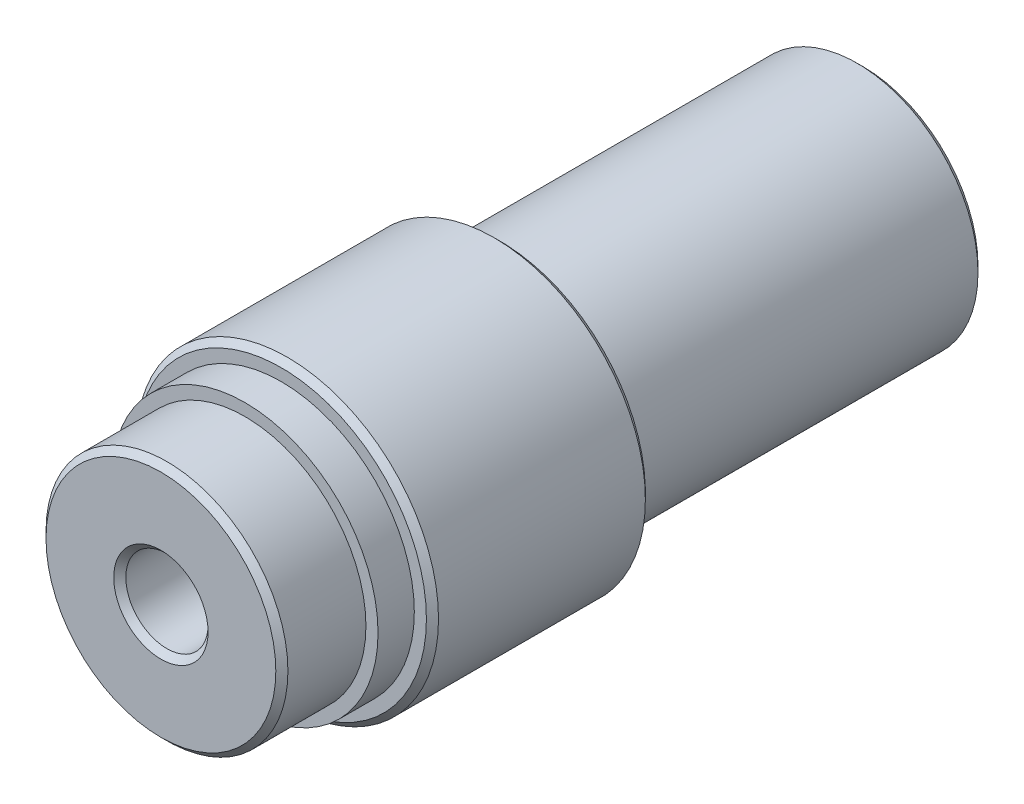
SolidWorks part; units mm, degrees
material "AISI 304"
ref_plane "Front" through (0, 0, 0) normal (0, 0, 1) x (1, 0, 0)
ref_plane "Top" through (0, 0, 0) normal (0, 1, 0) x (1, 0, 0)
ref_plane "Right" through (0, 0, 0) normal (1, 0, 0) x (0, 0, -1)
sketch "Çizim1" plane through (0, 0, 0) normal (1, 0, 0) x (0, 0, -1)
  line L0 (-29.025, 0) -> (29.025, 0)
  point P4 (0, 0)
  dimension "D1" = 58.05
other "Mil - configured CAP=25(1)"
ref_plane "Düzlem1" through (0, 0, 29.025) normal (0, 0, -1) x (0, 1, 0)
sketch "Sketch1" plane through (0, 0, 29.025) normal (0, 0, -1) x (0, 1, 0)
  circle A0 centre (0, 0) radius 12.5
  point P3 (0, 0)
  dimension "D1" = 25
sketch "Çizim3" plane through (0, 0, 0) normal (1, 0, 0) x (0, 0, -1)
  line L0 (29.025, 0) -> (32.8756, 0) construction
  line L1 (29.025, 12.5) -> (-0.975, 12.5)
  line L2 (29.025, 12.5) -> (29.025, 10)
  line L3 (29.025, 10) -> (-0.975, 10)
  line L4 (-0.975, 12.5) -> (-0.975, 10)
  line L5 (-29.025, 12.5) -> (-22.075, 12.5)
  line L6 (-29.025, 12.5) -> (-29.025, 10)
  line L7 (-29.025, 10) -> (-22.075, 10)
  line L8 (-22.075, 12.5) -> (-22.075, 10)
  line L9 (29.025, -12.5) -> (29.025, 12.5) construction
  dimension "D1" = 20
  dimension "D2" = 30
  dimension "D3" = 6.95
revolve "Kes-Döndür1" cut sketch "Çizim3" angle 360 about L0
hole_wizard "M8 Dişli Delik1" positions "Çizim5" profile "Çizim4" tap size "M8" standard "DIN"
sketch "Çizim5" plane through (0, 0, 29.025) normal (0, 0, 1) x (1, 0, 0)
  point P0 (0, 0)
sketch "Çizim4" plane through (0, 0, 29.025) normal (1, 0, 0) x (0, -1, 0)
  line L0 (0, 0) -> (0, 24.2929)
  line L1 (0, 24.2929) -> (3.4, 22.25)
  line L2 (3.4, 22.25) -> (3.4, 0)
  line L5 (3.4, 0) -> (0, 0)
  line L10 (0, 24.2929) -> (-3.4, 22.25) construction
  line L11 (0, -6.35) -> (0, 107.95) construction
  dimension "Tap Drill Dia." = 6.8
  dimension "Tap Drill Depth" = 22.25
  dimension "Drill Angle" = 118
cosmetic thread "Delik Dişi1" parameters "D1"=16, "D2"=8
mirror "Aynalama1" about plane through (0, 0, 0) normal (0, 0, 1) of "M8 Dişli Delik1"
cosmetic thread "Delik Dişi2" parameters "D1"=16, "D2"=8
chamfer "Pah1" distance 0.5 angle 45 5 edges at (10, 0, -29.025) (-3.4, 0, -29.025) (10, 0, 29.025) (3.4, 0, 29.025) (12.5, 0, 0.975)
chamfer "Pah2" distance 1.5 angle 45 1 edges at (12.5, 0, 22.075)
sketch "Çizim6" plane through (0, 0, 0) normal (1, 0, 0) x (0, 0, -1)
  line L0 (-1.475, 12.5) -> (-20.575, 12.5) construction
  line L1 (-22.075, 11) -> (-19.075, 11)
  line L2 (-22.075, 11) -> (-22.075, 12.5)
  line L3 (-22.075, 12.5) -> (-19.075, 12.5)
  line L4 (-19.075, 11) -> (-19.075, 12.5)
  line L5 (-29.025, 0) -> (-34.8798, 0) construction
  dimension "D1" = 3
revolve "Kes-Döndür2" cut sketch "Çizim6" angle 360 about L5
chamfer "Pah3" distance 0.5 angle 45 1 edges at (-12.5, 0, 19.075)
